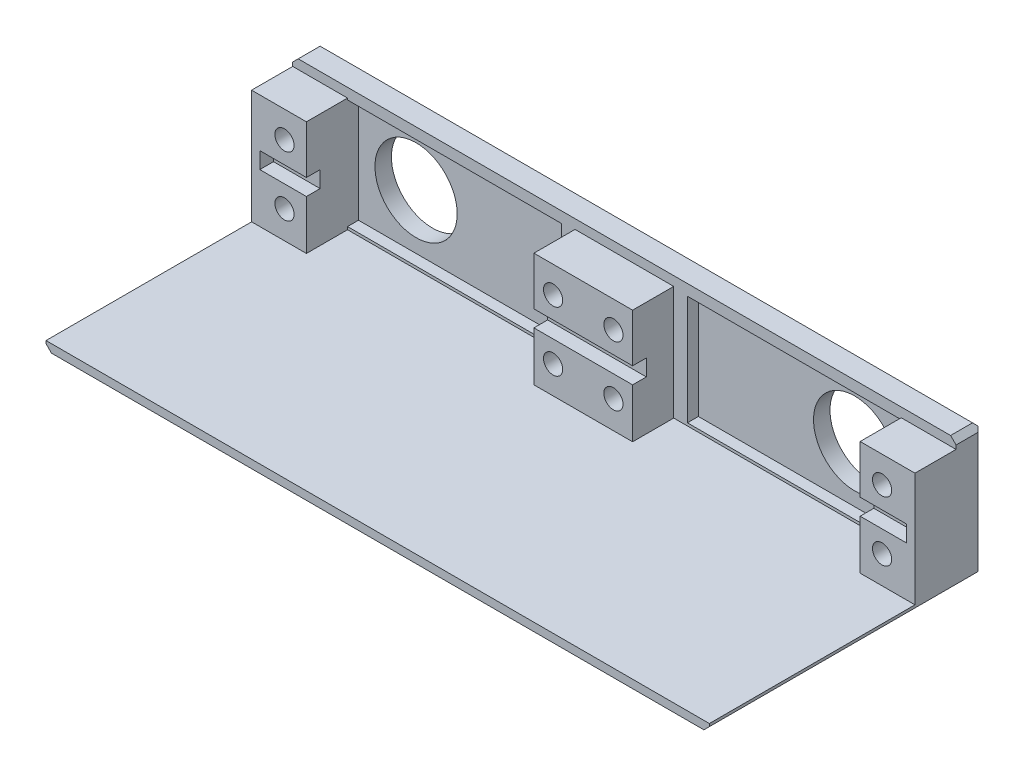
SolidWorks part; units mm, degrees
material "ABS"
ref_plane "Płaszczyzna przednia" through (0, 0, 0) normal (0, 0, 1) x (1, 0, 0)
ref_plane "Płaszczyzna górna" through (0, 0, 0) normal (0, 1, 0) x (1, 0, 0)
ref_plane "Płaszczyzna prawa" through (0, 0, 0) normal (1, 0, 0) x (0, 0, -1)
sketch "Szkic1" plane through (0, 0, 0) normal (0, 0, 1) x (1, 0, 0)
  line L0 (0, 0) -> (80, 0) construction
  line L2 (-20.5, 12) -> (100.5, 12)
  line L3 (-20.5, 12) -> (-20.5, -12)
  line L4 (-20.5, -12) -> (100.5, -12)
  line L5 (100.5, 12) -> (100.5, -12)
  line L6 (-20.5, 12) -> (100.5, -12) construction
  line L7 (-20.5, -12) -> (100.5, 12) construction
  circle A0 centre (0, 0) radius 7.5
  circle A1 centre (80, 0) radius 7.5
  point P5 (40, 0)
  dimension "D1" = 15
  dimension "D2" = 15
  dimension "D3" = 80
  dimension "D4" = 24
  dimension "D5" = 20.5
  dimension "D6" = 20.5
extrude "Dodanie-wyciągnięcie1" add sketch "Szkic1" along normal blind 3
sketch "Szkic2" plane through (0, 0, 3) normal (0, 0, 1) x (1, 0, 0)
  line L0 (28.5, 0) -> (0, 0) construction
  line L1 (-20.5, 12) -> (100.5, 12)
  line L2 (-20.5, 12) -> (-20.5, -12)
  line L3 (-20.5, -12) -> (100.5, -12)
  line L4 (100.5, 12) -> (100.5, -12)
  line L5 (-10.5, 10) -> (28.5, 10)
  line L6 (-10.5, 10) -> (-10.5, -10)
  line L7 (-10.5, -10) -> (28.5, -10)
  line L8 (28.5, 10) -> (28.5, -10)
  line L13 (40, 12) -> (40, -12) construction
  line L14 (90.5, -10) -> (51.5, -10)
  line L15 (51.5, 10) -> (51.5, -10)
  line L16 (90.5, 10) -> (51.5, 10)
  line L17 (90.5, 10) -> (90.5, -10)
  circle A0 centre (0, 0) radius 7.5 construction
  dimension "D3" = 10.5
  dimension "D1" = 20
  dimension "D2" = 39
  dimension "D4" = 23
extrude "Dodanie-wyciągnięcie2" add sketch "Szkic2" along normal blind 2
sketch "Szkic3" plane through (0, 0, 5) normal (0, 0, 1) x (1, 0, 0)
  line L0 (-20.5, 0) -> (100.5, 0) construction
  line L1 (-20.5, 10.5) -> (-10.5, 10.5)
  line L2 (-20.5, 10.5) -> (-20.5, -10.5)
  line L3 (-20.5, -10.5) -> (-10.5, -10.5)
  line L4 (-10.5, 10.5) -> (-10.5, -10.5)
  line L5 (-20.5, 10.5) -> (-10.5, -10.5) construction
  line L6 (-20.5, -10.5) -> (-10.5, 10.5) construction
  line L12 (31, 10.5) -> (49, 10.5)
  line L13 (-20.5, 12) -> (-20.5, -12) construction
  line L14 (100.5, -12) -> (100.5, 12) construction
  line L15 (31, 10.5) -> (31, -10.5)
  line L16 (31, -10.5) -> (49, -10.5)
  line L17 (49, 10.5) -> (49, -10.5)
  line L18 (40, 12) -> (40, -12) construction
  line L19 (100.5, 12) -> (-20.5, 12) construction
  line L20 (-20.5, -12) -> (100.5, -12) construction
  line L21 (100.5, -10.5) -> (90.5, -10.5)
  line L22 (90.5, 10.5) -> (90.5, -10.5)
  line L23 (100.5, 10.5) -> (90.5, 10.5)
  line L24 (100.5, 10.5) -> (100.5, -10.5)
  point P0 (-15.5, 0)
  point P9 (80, 0)
  dimension "D1" = 21
  dimension "D2" = 10.5
  dimension "D3" = 10
  dimension "D4" = 31
  dimension "D5" = 31
  dimension "D6" = 10.5
  dimension "D7" = 10
  dimension "D8" = 18
extrude "Dodanie-wyciągnięcie3" add sketch "Szkic3" along normal blind 5
sketch "Szkic5" plane through (0, 0, 10) normal (0, 0, 1) x (1, 0, 0)
  line L0 (-20.5, 0) -> (100.5, 0) construction
  line L1 (-20.5, 10.5) -> (-10.5, 10.5)
  line L2 (-20.5, 10.5) -> (-20.5, -10.5)
  line L3 (-20.5, -10.5) -> (-10.5, -10.5)
  line L4 (-10.5, 10.5) -> (-10.5, 1.5)
  line L5 (100.5, -10.5) -> (100.5, 10.5) construction
  line L6 (40, 12) -> (40, -12) construction
  line L7 (100.5, 12) -> (-20.5, 12) construction
  line L8 (-20.5, -12) -> (100.5, -12) construction
  line L9 (-10.5, -1.5) -> (-10.5, -10.5)
  line L10 (-10.5, 1.5) -> (-19, 1.5)
  line L12 (-10.5, -1.5) -> (-19, -1.5)
  line L13 (-19, 1.5) -> (-19, -1.5)
  line L14 (90.5, -1.5) -> (99, -1.5)
  line L15 (99, 1.5) -> (99, -1.5)
  line L16 (90.5, 1.5) -> (99, 1.5)
  line L17 (90.5, 10.5) -> (90.5, 1.5)
  line L18 (100.5, 10.5) -> (90.5, 10.5)
  line L19 (100.5, 10.5) -> (100.5, -10.5)
  line L20 (100.5, -10.5) -> (90.5, -10.5)
  line L21 (90.5, -1.5) -> (90.5, -10.5)
  line L22 (31, -1.5) -> (31, -10.5)
  line L23 (31, 10.5) -> (49, 10.5)
  line L24 (31, 10.5) -> (31, 1.5)
  line L25 (31, -10.5) -> (49, -10.5)
  line L26 (49, 10.5) -> (49, 1.5)
  line L27 (31, 1.5) -> (49, 1.5)
  line L29 (31, -1.5) -> (49, -1.5)
  line L31 (49, -1.5) -> (49, -10.5)
  dimension "D1" = 3
  dimension "D2" = 8.5
extrude "Dodanie-wyciągnięcie4" add sketch "Szkic5" along normal offset from surface (2.5 mm away) 9.5 up to face at (7.5, 0, 3) offset beyond the face yes
sketch "Szkic6" plane through (0, 0, 12.5) normal (0, 0, 1) x (1, 0, 0)
  line L0 (-20.5, 0) -> (100.5, 0) construction
  line L1 (-20.5, 10.5) -> (-20.5, -10.5) construction
  line L2 (100.5, -10.5) -> (100.5, 10.5) construction
  line L3 (-10.5, 10) -> (-10.5, -10) construction
  line L4 (31, 10.5) -> (31, 1.5) construction
  line L5 (40, 12) -> (40, -12) construction
  line L6 (100.5, 12) -> (-20.5, 12) construction
  line L7 (-20.5, -12) -> (100.5, -12) construction
  circle A0 centre (-14.5, 5.45) radius 1.75
  circle A1 centre (34.5, 5.45) radius 1.75
  circle A2 centre (34.5, -5.45) radius 1.75
  circle A3 centre (-14.5, -5.45) radius 1.75
  circle A4 centre (45.5, 5.45) radius 1.75
  circle A5 centre (45.5, -5.45) radius 1.75
  circle A6 centre (94.5, -5.45) radius 1.75
  circle A7 centre (94.5, 5.45) radius 1.75
  dimension "D1" = 3.5
  dimension "D2" = 5.45
  dimension "D3" = 4
  dimension "D4" = 3.5
  dimension "D5" = 3.5
extrude "Wytnij-wyciągnięcie1" cut sketch "Szkic6" against normal up to next
sketch "Szkic7" plane through (0, 0, 0) normal (0, 0, -1) x (-1, 0, 0)
  circle A0 centre (-94.5, 5.45) radius 3.75
  circle A2 centre (-94.5, -5.45) radius 3.75
  circle A6 centre (14.5, 5.45) radius 3.75
  circle A7 centre (14.5, -5.45) radius 3.75
  circle M9 centre (14.5, -5.45) radius 1.75
  circle M13 centre (-94.5, -5.45) radius 1.75
  circle M14 centre (-94.5, 5.45) radius 1.75
  circle M15 centre (14.5, 5.45) radius 1.75
  dimension "D1" = 7.5
extrude "Wytnij-wyciągnięcie2" cut sketch "Szkic7" against normal offset from surface (1.5 mm away) 1.5 contours A7 M9 | A6 M15 | A2 M13 | A0 M14 up to face at (87.5, 0, 3)
sketch "Szkic9" plane through (0, 0, 0) normal (0, 0, -1) x (-1, 0, 0)
  line L1 (-40.8835, 7.95) -> (-39.1165, 7.95)
  line L2 (-40.8835, 2.95) -> (-39.1165, 2.95)
  line L4 (-45.5, 5.45) -> (-34.5, 5.45) construction
  line L5 (6.875, 0) -> (-6.875, 0) construction
  line L6 (-40.8835, -7.95) -> (-39.1165, -7.95)
  line L7 (-40.8835, -2.95) -> (-39.1165, -2.95)
  arc A0 (-40.8835, 7.95) -> (-40.8835, 2.95) centre (-45.5, 5.45) ccw
  arc A1 (-39.1165, 2.95) -> (-39.1165, 7.95) centre (-34.5, 5.45) ccw
  arc A4 (-40.8835, -7.95) -> (-40.8835, -2.95) centre (-45.5, -5.45) cw
  arc A5 (-39.1165, -2.95) -> (-39.1165, -7.95) centre (-34.5, -5.45) cw
  dimension "D1" = 10.5
  dimension "D2" = 5
extrude "Wytnij-wyciągnięcie4" cut sketch "Szkic9" against normal offset from surface (1.5 mm away) 1.5 up to face at (7.5, 0, 3)
fillet "Zaokrąglenie1" radius 1.5 8 edges at (39.1165, -7.95, 0.75) (40.8835, -7.95, 0.75) (39.1165, -2.95, 0.75) (40.8835, -2.95, 0.75) (39.1165, 2.95, 0.75) (40.8835, 2.95, 0.75) (40.8835, 7.95, 0.75) (39.1165, 7.95, 0.75)
sketch "Szkic10" plane through (0, 10.5, 0) normal (0, 1, 0) x (1, 0, 0)
  line L1 (-20.5, -5) -> (-10.5, -5)
  line L2 (-20.5, -5) -> (-20.5, -12.5)
  line L3 (-20.5, -12.5) -> (-10.5, -12.5)
  line L4 (-10.5, -5) -> (-10.5, -12.5)
  line L5 (31, -5) -> (49, -5)
  line L6 (31, -5) -> (31, -12.5)
  line L7 (31, -12.5) -> (49, -12.5)
  line L8 (49, -5) -> (49, -12.5)
  line L9 (90.5, -5) -> (100.5, -5)
  line L10 (90.5, -5) -> (90.5, -12.5)
  line L11 (90.5, -12.5) -> (100.5, -12.5)
  line L12 (100.5, -5) -> (100.5, -12.5)
extrude "Wytnij-wyciągnięcie5" cut sketch "Szkic10" against normal blind 0.2
sketch "Szkic11" plane through (0, 0, 5) normal (0, 0, 1) x (1, 0, 0)
  line L0 (100.5, -12) -> (100.5, -10.5) construction
  line L1 (-20.5, -12) -> (100.5, -12)
  line L2 (-20.5, -12) -> (-20.5, -10.5)
  line L3 (-20.5, -10.5) -> (100.5, -10.5)
  line L4 (100.5, -12) -> (100.5, -10.5)
  dimension "D1" = 1.5
extrude "Dodanie-wyciągnięcie5" add sketch "Szkic11" along normal blind 45
chamfer "Sfazowanie1" distance 1 angle 45 4 edges at (40, -12, 0) (40, 12, 0) (100.5, 0, 0) (-20.5, 0, 0)
chamfer "Sfazowanie2" distance 1 angle 45 4 edges at (-20.5, -12, 25.5) (-20.5, 12, 3) (100.5, -12, 25.5) (100.5, 12, 3)
